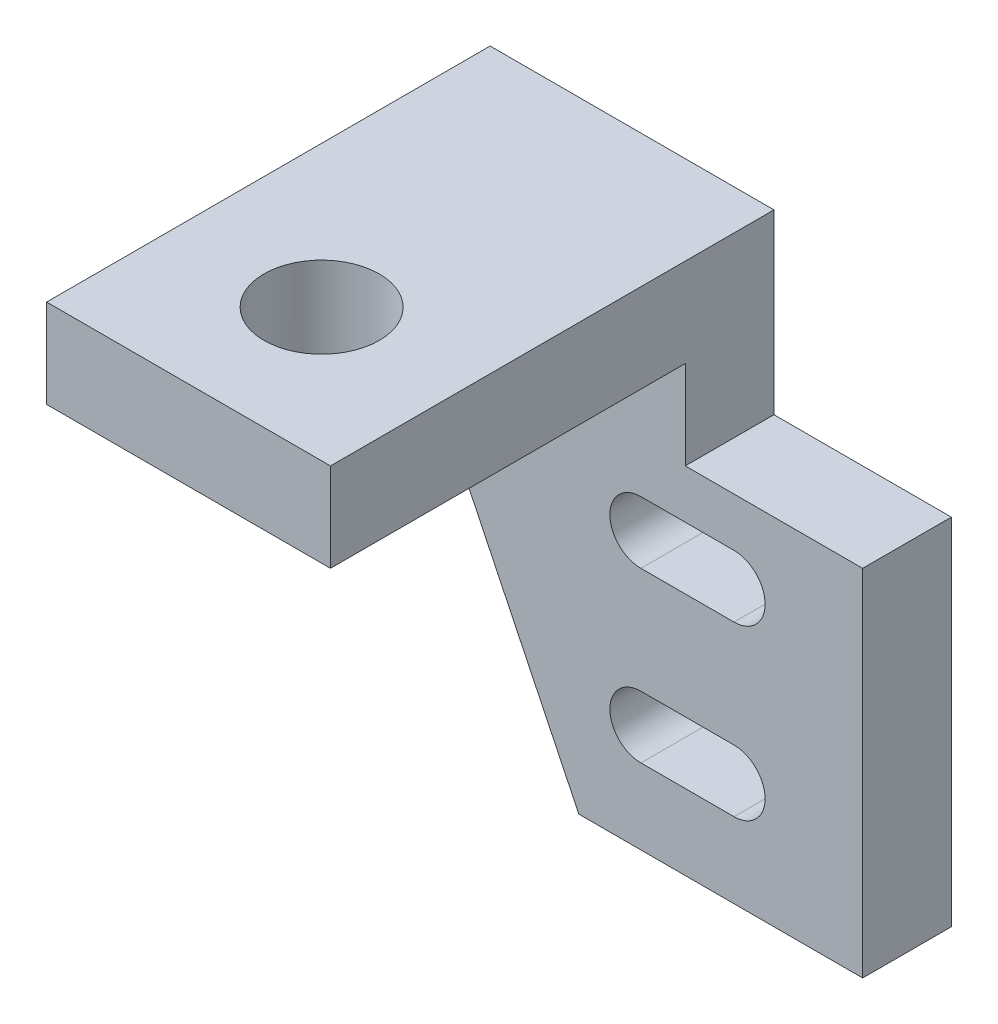
SolidWorks part; units mm, degrees
ref_plane "Piano frontale" through (0, 0, 0) normal (0, 0, 1) x (1, 0, 0)
ref_plane "Piano superiore" through (0, 0, 0) normal (0, 1, 0) x (1, 0, 0)
ref_plane "Piano destro" through (0, 0, 0) normal (1, 0, 0) x (0, 0, -1)
sketch "Schizzo1" plane through (0, 0, 0) normal (0, 0, 1) x (1, 0, 0)
  line L0 (-16, 0) -> (0, 0)
  line L1 (0, 0) -> (0, -10)
  line L3 (0, -10) -> (10, -10)
  line L4 (10, -10) -> (10, -30)
  line L5 (10, -30) -> (-6, -30)
  line L6 (-6, -30) -> (-16, -9.2952)
  line L7 (-16, -9.2952) -> (-16, 0)
  line L8 (2.75, -22.25) -> (-2.5, -22.25)
  line L9 (2.75, -25.75) -> (-2.5, -25.75)
  line L10 (2.75, -12.75) -> (-2.5, -12.75)
  line L11 (2.75, -16.25) -> (-2.5, -16.25)
  arc A0 (2.75, -25.75) -> (2.75, -22.25) centre (2.75, -24) ccw
  arc A1 (-2.5, -22.25) -> (-2.5, -25.75) centre (-2.5, -24) ccw
  arc A2 (2.75, -16.25) -> (2.75, -12.75) centre (2.75, -14.5) ccw
  arc A3 (-2.5, -12.75) -> (-2.5, -16.25) centre (-2.5, -14.5) ccw
  dimension "D2" = 20
  dimension "D6" = 1.75
  dimension "D10" = 7.25
  dimension "D1" = 16
  dimension "D3" = 10
  dimension "D4" = 30
  dimension "D5" = 16
  dimension "D7" = 5.25
  dimension "D8" = 4.25
  dimension "D9" = 6
  dimension "D11" = 7.25
  dimension "D12" = 20.7048
extrude "Estrusione-Estrusione1" add sketch "Schizzo1" along normal blind 5
sketch "Schizzo2" plane through (0, 0, 5) normal (0, 0, 1) x (1, 0, 0)
  line L0 (-16, 0) -> (-16, -5)
  line L1 (-16, 0) -> (-16, -9.2952) construction
  line L2 (-16, -5) -> (0, -5)
  line L3 (0, -10) -> (0, 0) construction
  line L4 (0, -5) -> (0, 0)
  line L5 (0, 0) -> (-16, 0)
  dimension "D1" = 5
extrude "Estrusione-Estrusione2" add sketch "Schizzo2" along normal blind 20
sketch "Schizzo3" plane through (0, -5, 0) normal (0, -1, 0) x (1, 0, 0)
  line L2 (-8, 25) -> (-8, 4.0351) construction
  line L3 (-16, 25) -> (0, 25) construction
  circle A0 centre (-8, 17.5) radius 3.25
  dimension "D1" = 6.5
  dimension "D2" = 7.5
extrude "Taglio-Estrusione1" cut sketch "Schizzo3" against normal up to next
